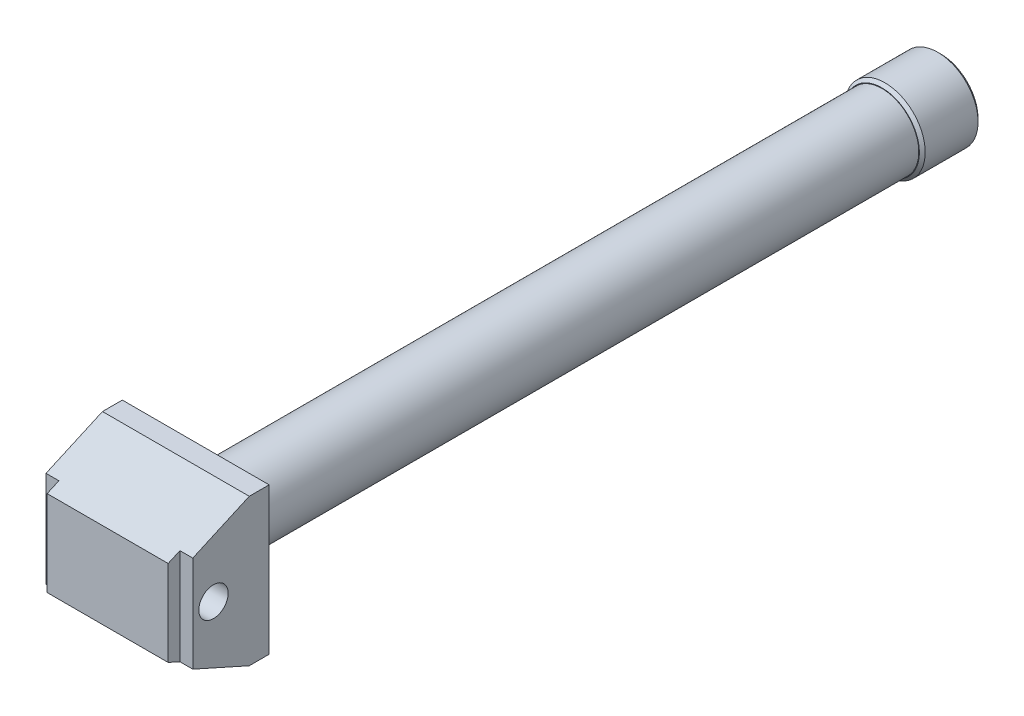
SolidWorks part; units mm, degrees
ref_plane "Front Plane" through (0, 0, 0) normal (0, 0, 1) x (1, 0, 0)
ref_plane "Top Plane" through (0, 0, 0) normal (0, 1, 0) x (1, 0, 0)
ref_plane "Right Plane" through (0, 0, 0) normal (1, 0, 0) x (0, 0, -1)
sketch "Sketch1" plane through (0, 0, 0) normal (0, 0, 1) x (1, 0, 0)
  line L1 (125, 125) -> (-125, 125)
  line L2 (125, 125) -> (125, -125)
  line L3 (125, -125) -> (-125, -125)
  line L4 (-125, 125) -> (-125, -125)
  line L5 (125, 125) -> (-125, -125) construction
  line L6 (125, -125) -> (-125, 125) construction
  point P0 (0, 0)
  dimension "D1" = 250
extrude "Boss-Extrude1" add sketch "Sketch1" along normal blind 150
sketch "Sketch2" plane through (0, 0, 0) normal (0, 0, -1) x (-1, 0, 0)
  circle A0 centre (0, 0) radius 62.5
  dimension "D1" = 125
extrude "Boss-Extrude2" add sketch "Sketch2" along normal blind 1269
sketch "Sketch3" plane through (-125, 0, 0) normal (-1, 0, 0) x (0, 0, 1)
  line L0 (150, 125) -> (150, -125) construction
  line L1 (150, -73) -> (150, -125)
  line L2 (150, -125) -> (33.82, -125)
  line L3 (150, -125) -> (0, -125) construction
  line L4 (33.82, -125) -> (150, -73)
  line L5 (0, 0) -> (150, 0) construction
  line L6 (150, 125) -> (33.82, 125)
  line L7 (150, 73) -> (150, 125)
  line L8 (33.82, 125) -> (150, 73)
  circle A0 centre (94.75, 0) radius 25
  dimension "D1" = 50
  dimension "D2" = 55.25
  dimension "D3" = 116.18
  dimension "D4" = 52
extrude "Cut-Extrude1" cut sketch "Sketch3" against normal through all
sketch "Sketch4" plane through (0, 0, -1269) normal (0, 0, -1) x (-1, 0, 0)
  circle A0 centre (0, 0) radius 37.5
  dimension "D1" = 75
extrude "Cut-Extrude2" cut sketch "Sketch4" against normal up to surface (1269 mm away) up to face at (-62.5, 0, 0)
sketch "Sketch5" plane through (0, 0, 150) normal (0, 0, 1) x (1, 0, 0)
  line L0 (-125, 73) -> (-125, -73) construction
  line L1 (-211.5116, 161.2275) -> (-103.06, 161.2275)
  line L2 (-211.5116, 161.2275) -> (-211.5116, -159.4876)
  line L3 (-211.5116, -159.4876) -> (-103.06, -159.4876)
  line L4 (-103.06, 161.2275) -> (-103.06, -159.4876)
  line L5 (0, 125) -> (0, -125) construction
  line L6 (125, 125) -> (-125, 125) construction
  line L7 (125, -125) -> (-125, -125) construction
  line L8 (211.5116, -159.4876) -> (103.06, -159.4876)
  line L9 (103.06, 161.2275) -> (103.06, -159.4876)
  line L10 (211.5116, 161.2275) -> (103.06, 161.2275)
  line L11 (211.5116, 161.2275) -> (211.5116, -159.4876)
  point P11 (0, 0)
  dimension "D1" = 21.94
extrude "Cut-Extrude3" cut sketch "Sketch5" against normal blind 20
sketch "Sketch6" plane through (0, 0, -1269) normal (0, 0, -1) x (-1, 0, 0)
  circle A0 centre (0, 0) radius 68.445
  circle A1 centre (0, 0) radius 62.5 construction
  circle A2 centre (0, 0) radius 62.5
  dimension "D1" = 136.89
extrude "Boss-Extrude3" add sketch "Sketch6" against normal blind 100 separate body
chamfer "Chamfer1" distance 5 angle 45 2 edges at (-68.445, 0, -1269) (-68.445, 0, -1169)
chamfer "Chamfer2" distance 5 angle 45 1 edges at (-37.5, 0, -1269)
